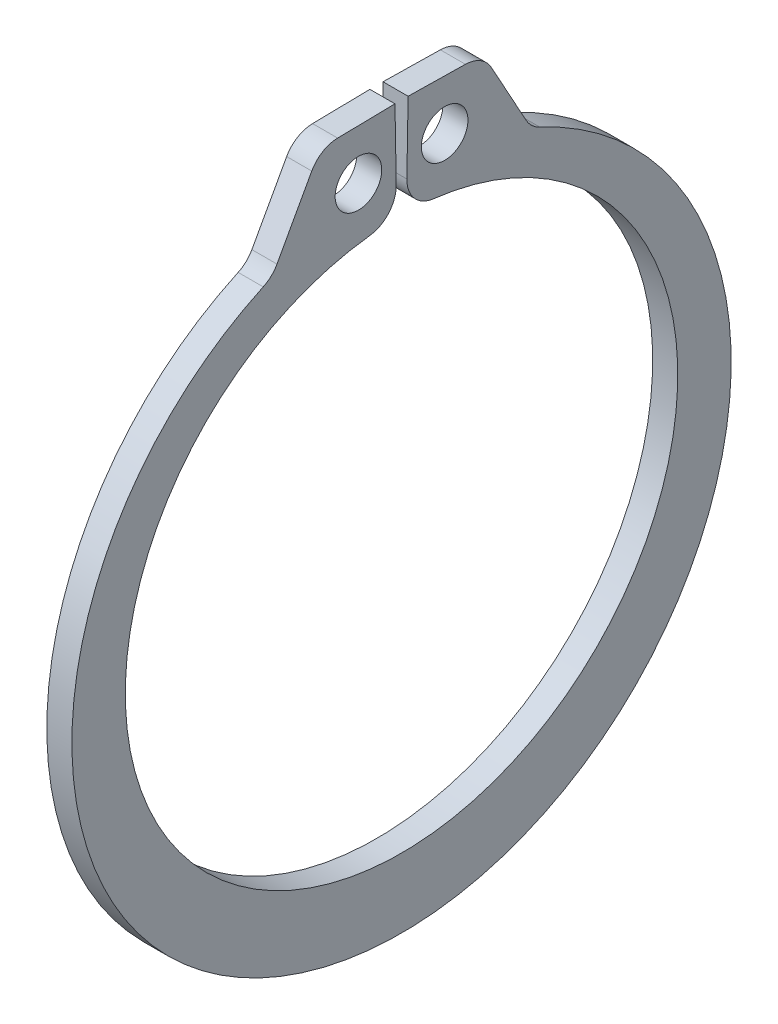
SolidWorks part; units mm, degrees
material "Cast Carbon Steel"
ref_plane "Front" through (0, 0, 0) normal (0, 0, 1) x (1, 0, 0)
ref_plane "Top" through (0, 0, 0) normal (0, 1, 0) x (1, 0, 0)
ref_plane "Right" through (0, 0, 0) normal (1, 0, 0) x (0, 0, -1)
sketch "Sketch1" plane through (0, 0, 0) normal (1, 0, 0) x (0, 0, -1)
  line L0 (0, 0) -> (0, 11.7475) construction
  line L1 (-0.205, 11.7457) -> (-0.2791, 15.9869)
  line L2 (0.2791, 15.9869) -> (3.4599, 15.9313)
  line L3 (3.4599, 15.9313) -> (5.5053, 12.2152)
  line L4 (0.205, 11.7457) -> (0.2791, 15.9869)
  line L5 (-0.2791, 15.9869) -> (-3.4599, 15.9313)
  line L6 (-3.4599, 15.9313) -> (-5.5053, 12.2152)
  line L7 (-5.5053, 12.2152) -> (-4.8269, 10.71) construction
  line L8 (5.5053, 12.2152) -> (4.8269, 10.71) construction
  line L9 (0, -11.7475) -> (0, -14.6939) construction
  line L10 (-3.4599, 15.9313) -> (-0.205, 11.7457) construction
  line L11 (0, 11.7475) -> (0, 15.9893) construction
  line L12 (-11.7475, 0) -> (11.7475, 0) construction
  circle A0 centre (0, 0) radius 11.7475 construction
  arc A1 (-0.205, 11.7457) -> (0.205, 11.7457) centre (0, 0) ccw
  circle A4 centre (-1.8325, 13.8385) radius 0.9906
  circle A5 centre (1.8325, 13.8385) radius 0.9906
  arc A6 (-5.5053, 12.2152) -> (5.5053, 12.2152) centre (0, -0.6762) ccw construction
  point P0 (0, -14.6939)
  dimension "Ring ID" = 23.495
  dimension "Hole Diameter" = 1.9812
  dimension "Min. Sec." = 1.651
  dimension "Max. Sec." = 2.9464
  dimension "Lug Height" = 4.2418
  dimension "D2" = 3.1813
  dimension "Angle" = 1
sketch "Sketch2" plane through (0, 0, 0) normal (0, 1, 0) x (1, 0, 0)
  line L0 (-0.5334, -14.0014) -> (0.5334, -14.0014) construction
  line L1 (0, -14.0177) -> (0, 14.0177) construction
  point P8 (0, -14.0014)
  dimension "Ring Thickness" = 1.0668
sketch "Sketch3" plane through (0, 0, 0) normal (1, 0, 0) x (0, 0, -1)
  line L0 (-3.4599, 15.9313) -> (-5.5053, 12.2152) construction
  line L1 (-3.4599, 15.9313) -> (-5.5053, 12.2152)
  line L2 (-0.2791, 15.9869) -> (-3.4599, 15.9313) construction
  line L3 (-0.2791, 15.9869) -> (-3.4599, 15.9313)
  line L4 (-0.205, 11.7457) -> (-0.2791, 15.9869) construction
  line L5 (-0.205, 11.7457) -> (-0.2791, 15.9869)
  line L6 (0.205, 11.7457) -> (0.2791, 15.9869) construction
  line L7 (0.205, 11.7457) -> (0.2791, 15.9869)
  line L8 (0.2791, 15.9869) -> (3.4599, 15.9313) construction
  line L9 (0.2791, 15.9869) -> (3.4599, 15.9313)
  line L10 (3.4599, 15.9313) -> (5.5053, 12.2152) construction
  line L11 (3.4599, 15.9313) -> (5.5053, 12.2152)
  arc A0 (-5.5053, 12.2152) -> (5.5053, 12.2152) centre (0, -0.6762) ccw construction
  arc A1 (-5.5053, 12.2152) -> (5.5053, 12.2152) centre (0, -0.6762) ccw
  arc A2 (-0.205, 11.7457) -> (0.205, 11.7457) centre (0, 0) ccw construction
  arc A3 (-0.205, 11.7457) -> (0.205, 11.7457) centre (0, 0) ccw
  circle A4 centre (-1.8325, 13.8385) radius 0.9906 construction
  circle A5 centre (-1.8325, 13.8385) radius 0.9906
  circle A6 centre (1.8325, 13.8385) radius 0.9906 construction
  circle A7 centre (1.8325, 13.8385) radius 0.9906
extrude "Boss-Extrude1" add sketch "Sketch3" along normal up to vertex (0.5334 mm away) and the other way up to vertex (0.5334 mm away) up to point (0.5334, 0, 14.0014) other way up to point (-0.5334, 0, 14.0014)
fillet "Fillet1" radius 1.2827 6 edges at (0, 12.2152, -5.5053) (0, 15.9313, -3.4599) (0, 11.7457, -0.205) (0, 11.7457, 0.205) (0, 15.9313, 3.4599) (0, 12.2152, 5.5053)
sketch "Sketch4" plane through (0, 0, 0) normal (1, 0, 0) x (0, 0, -1)
  line L0 (-10.1736, 5.8738) -> (0, 0) construction
  line L1 (0, 0) -> (0, 11.7475) construction
  line L2 (0, 15.9893) -> (0, 11.7475) construction
  arc A0 (-0.205, 11.7457) -> (0.205, 11.7457) centre (0, 0) ccw construction
  point P0 (0, 0)
  point P1 (-10.1736, 5.8738)
  dimension "D1" = 60
equation "\"D2@Sketch1\" = \"Lug Height@Sketch1\" * .75"
